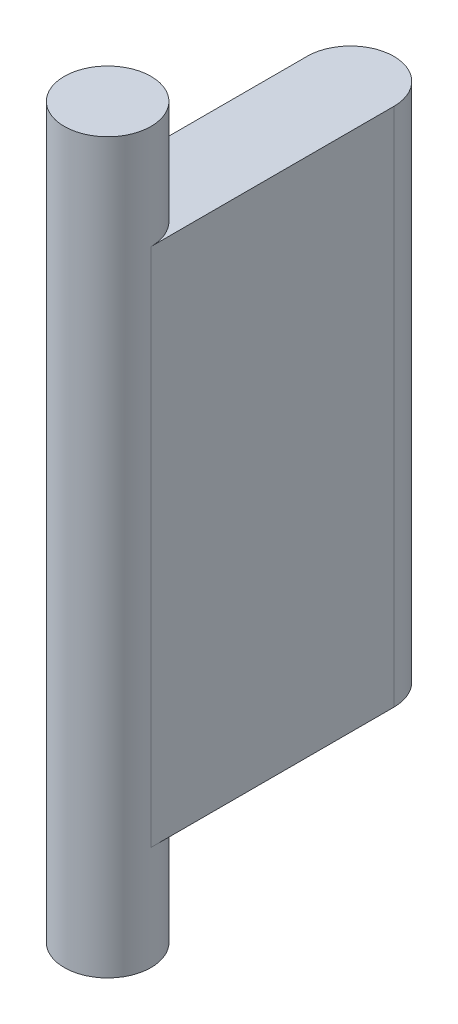
SolidWorks part; units mm, degrees
ref_plane "前视基准面" through (0, 0, 0) normal (0, 0, 1) x (1, 0, 0)
ref_plane "上视基准面" through (0, 0, 0) normal (0, 1, 0) x (1, 0, 0)
ref_plane "右视基准面" through (0, 0, 0) normal (1, 0, 0) x (0, 0, -1)
sketch "草图1" plane through (0, 0, 0) normal (0, 1, 0) x (1, 0, 0)
  line L0 (0, 0) -> (0, 7) construction
  line L1 (-1.25, 0) -> (-1.25, 7)
  line L2 (1.25, 0) -> (1.25, 7)
  arc A1 (-1.25, 0) -> (1.25, 0) centre (0, 0) ccw
  arc A2 (1.25, 7) -> (-1.25, 7) centre (0, 7) ccw
  point P3 (0, 3.5)
  dimension "D1" = 1.25
  dimension "D2" = 7
extrude "凸台-拉伸1" add sketch "草图1" along normal blind 15
sketch "草图2" plane through (0, 15, 0) normal (0, 1, 0) x (1, 0, 0)
  circle A0 centre (0, 0) radius 1.25
  dimension "D1" = 2.5
extrude "凸台-拉伸2" add sketch "草图2" along normal blind 3
sketch "草图3" plane through (0, 0, 0) normal (0, -1, 0) x (1, 0, 0)
  circle A0 centre (0, 0) radius 1.25
  dimension "D1" = 2.5
extrude "凸台-拉伸3" add sketch "草图3" along normal blind 3
